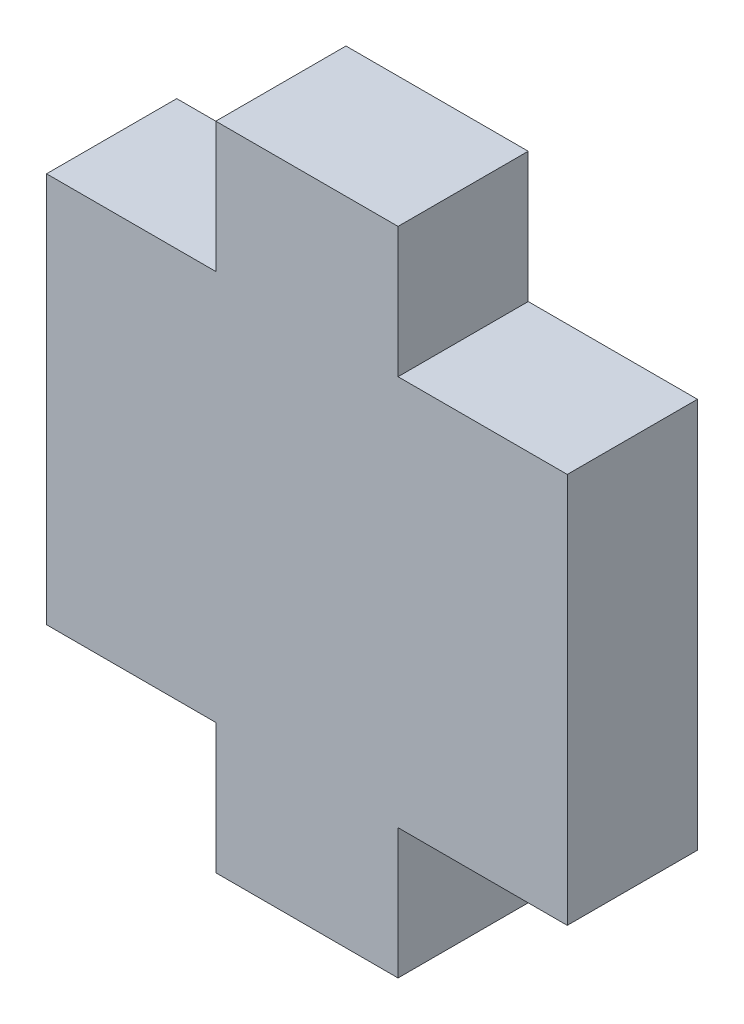
SolidWorks part; units mm, degrees
material "Acrylic (Medium-high impact)"
ref_plane "Front Plane" through (0, 0, 0) normal (0, 0, 1) x (1, 0, 0)
ref_plane "Top Plane" through (0, 0, 0) normal (0, 1, 0) x (1, 0, 0)
ref_plane "Right Plane" through (0, 0, 0) normal (1, 0, 0) x (0, 0, -1)
sketch "Sketch1" plane through (0, 0, 0) normal (0, 0, 1) x (1, 0, 0)
  line L0 (-10, -7.5) -> (-10, 7.5)
  line L1 (-10, 7.5) -> (-3.5, 7.5)
  line L2 (-3.5, 7.5) -> (-3.5, 12.5)
  line L3 (-3.5, 12.5) -> (3.5, 12.5)
  line L4 (3.5, 12.5) -> (3.5, 7.5)
  line L5 (3.5, 7.5) -> (10, 7.5)
  line L6 (10, 7.5) -> (10, -7.5)
  line L7 (10, -7.5) -> (3.5, -7.5)
  line L8 (3.5, -7.5) -> (3.5, -12.5)
  line L9 (3.5, -12.5) -> (-3.5, -12.5)
  line L10 (-3.5, -12.5) -> (-3.5, -7.5)
  line L11 (-3.5, -7.5) -> (-10, -7.5)
  point P14 (0, 12.5)
  point P15 (0, -12.5)
  point P17 (10, 0)
  dimension "D1" = 25
  dimension "D2" = 5
  dimension "D3" = 5
  dimension "D4" = 20
  dimension "D5" = 10
  dimension "D6" = 7
extrude "Boss-Extrude1" add sketch "Sketch1" along normal blind 5
